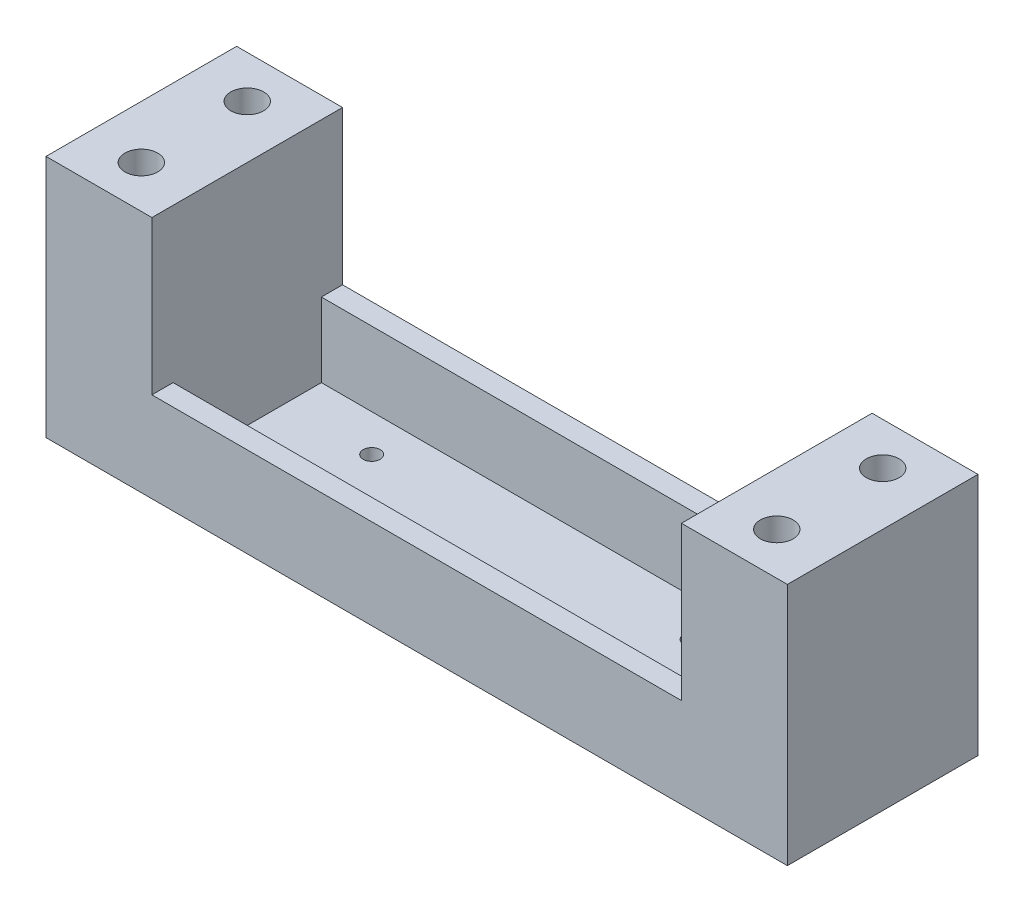
SolidWorks part; units mm, degrees
ref_plane "Plan de face" through (0, 0, 0) normal (0, 0, 1) x (1, 0, 0)
ref_plane "Plan de dessus" through (0, 0, 0) normal (0, 1, 0) x (1, 0, 0)
ref_plane "Plan de droite" through (0, 0, 0) normal (1, 0, 0) x (0, 0, -1)
sketch "Esquisse5" plane through (0, 0, 0) normal (0, 0, 1) x (1, 0, 0)
  line L0 (0, 0) -> (0, 46)
  line L1 (0, 46) -> (20, 46)
  line L2 (20, 46) -> (20, 17)
  line L3 (20, 17) -> (120, 17)
  line L4 (120, 17) -> (120, 46)
  line L5 (120, 46) -> (140, 46)
  line L6 (140, 46) -> (140, 0)
  line L7 (140, 0) -> (0, 0)
  dimension "D1" = 20
  dimension "D2" = 140
  dimension "D3" = 17
  dimension "D4" = 46
extrude "Boss.-Extru.1" add sketch "Esquisse5" along normal blind 36
sketch "Esquisse6" plane through (0, 17, 0) normal (0, 1, 0) x (1, 0, 0)
  line L0 (20, -4) -> (120, -4)
  line L1 (20, -36) -> (20, 0) construction
  line L3 (120, -36) -> (120, 0) construction
  line L5 (120, -4) -> (120, -32)
  line L6 (120, -32) -> (20, -32)
  line L9 (20, -32) -> (20, -4)
  dimension "D1" = 4
  dimension "D2" = 28
extrude "Enlèv. mat.-Extru.1" cut sketch "Esquisse6" against normal blind 14
sketch "Esquisse7" plane through (0, 3, 0) normal (0, 1, 0) x (1, 0, 0)
  line L0 (0, -18) -> (140, -18) construction
  line L1 (0, -36) -> (0, 0) construction
  line L2 (140, -36) -> (140, 0) construction
  circle A0 centre (36.5, -11) radius 1.6
  circle A1 centre (97, -11) radius 1.6
  circle A2 centre (97, -25) radius 1.6
  circle A3 centre (36.5, -25) radius 1.6
  dimension "D1" = 3.2
  dimension "D2" = 16.5
  dimension "D3" = 7
  dimension "D4" = 7
  dimension "D5" = 23
extrude "Enlèv. mat.-Extru.2" cut sketch "Esquisse7" against normal up to next
sketch "Esquisse8" plane through (0, 46, 0) normal (0, 1, 0) x (1, 0, 0)
  line L0 (10, -8) -> (10, -28) construction
  line L2 (0, -36) -> (0, 0) construction
  line L3 (70, 0) -> (70, -36) construction
  line L4 (10, -18) -> (0, -18) construction
  line L6 (120, 0) -> (20, 0) construction
  line L7 (120, -36) -> (20, -36) construction
  circle A0 centre (10, -8) radius 3.1
  circle A1 centre (10, -28) radius 3.1
  circle A2 centre (130, -28) radius 3.1
  circle A3 centre (130, -8) radius 3.1
  dimension "D3" = 6.2
  dimension "D4" = 6.2
  dimension "D1" = 10
  dimension "D5" = 20
extrude "Enlèv. mat.-Extru.3" cut sketch "Esquisse8" against normal up to next
sketch "Esquisse9" plane through (0, 0, 0) normal (0, -1, 0) x (1, 0, 0)
  line L0 (140, 36) -> (140, 0) construction
  line L1 (124.9, 5.0555) -> (130, 2.111)
  line L2 (130, 2.111) -> (135.1, 5.0555)
  line L3 (135.1, 5.0555) -> (135.1, 10.9445)
  line L4 (135.1, 10.9445) -> (130, 13.889)
  line L5 (130, 13.889) -> (124.9, 10.9445)
  line L6 (124.9, 10.9445) -> (124.9, 5.0555)
  line L7 (140, 18) -> (0, 18) construction
  line L8 (0, 36) -> (0, 0) construction
  line L9 (70, 0) -> (70, 36) construction
  line L10 (0, 0) -> (140, 0) construction
  line L11 (0, 36) -> (140, 36) construction
  line L12 (124.9, 25.0555) -> (124.9, 30.9445)
  line L13 (130, 22.111) -> (124.9, 25.0555)
  line L14 (135.1, 25.0555) -> (130, 22.111)
  line L15 (135.1, 30.9445) -> (135.1, 25.0555)
  line L16 (130, 33.889) -> (135.1, 30.9445)
  line L17 (124.9, 30.9445) -> (130, 33.889)
  line L18 (15.1, 30.9445) -> (10, 33.889)
  line L19 (10, 33.889) -> (4.9, 30.9445)
  line L20 (4.9, 30.9445) -> (4.9, 25.0555)
  line L21 (4.9, 25.0555) -> (10, 22.111)
  line L22 (10, 22.111) -> (15.1, 25.0555)
  line L23 (15.1, 25.0555) -> (15.1, 30.9445)
  line L24 (15.1, 10.9445) -> (15.1, 5.0555)
  line L25 (10, 13.889) -> (15.1, 10.9445)
  line L26 (4.9, 10.9445) -> (10, 13.889)
  line L27 (4.9, 5.0555) -> (4.9, 10.9445)
  line L28 (10, 2.111) -> (4.9, 5.0555)
  line L29 (15.1, 5.0555) -> (10, 2.111)
  circle A0 centre (130, 8) radius 5.1 construction
  circle A1 centre (130, 28) radius 5.1 construction
  circle A2 centre (10, 28) radius 5.1 construction
  circle A3 centre (10, 8) radius 5.1 construction
  dimension "D1" = 10.2
extrude "Enlèv. mat.-Extru.4" cut sketch "Esquisse9" against normal blind 5.5
